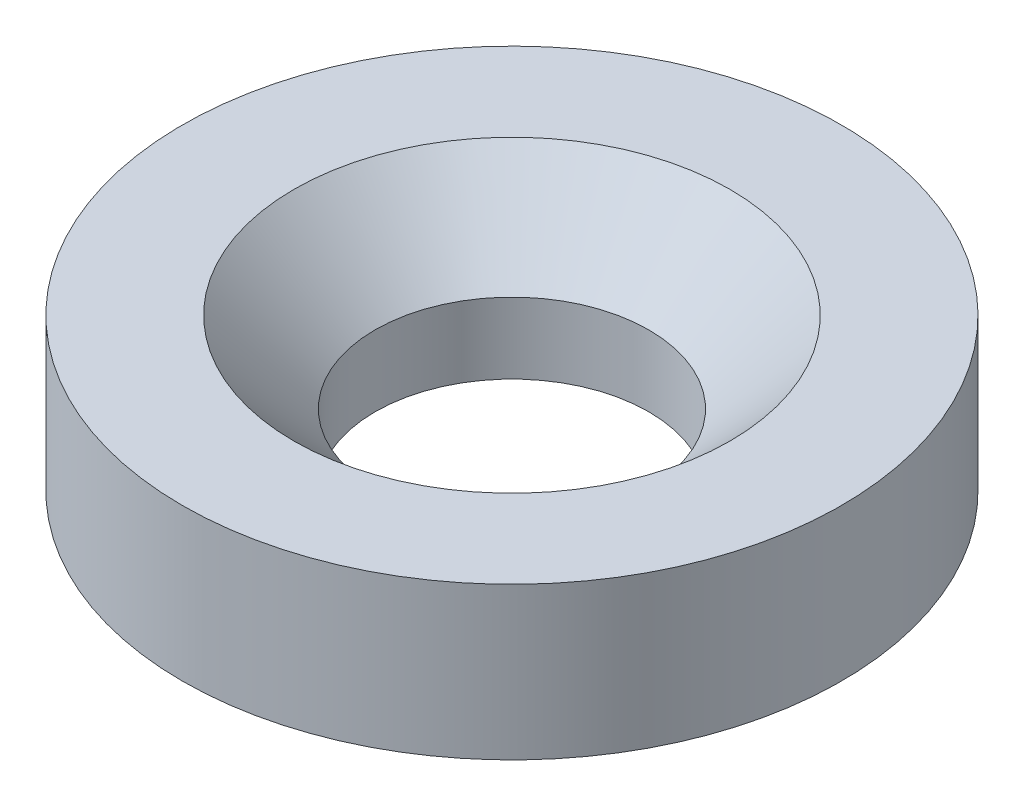
SolidWorks part; units mm, degrees
ref_plane "정면" through (0, 0, 0) normal (0, 0, 1) x (1, 0, 0)
ref_plane "윗면" through (0, 0, 0) normal (0, 1, 0) x (1, 0, 0)
ref_plane "우측면" through (0, 0, 0) normal (1, 0, 0) x (0, 0, -1)
sketch "스케치1" plane through (0, 0, 0) normal (0, 1, 0) x (1, 0, 0)
  circle A0 centre (0, 0) radius 3.25
  dimension "D1" = 6.5
extrude "보스-돌출1" add sketch "스케치1" along normal blind 1.5
sketch "스케치2" plane through (0, 1.5, 0) normal (0, 1, 0) x (1, 0, 0)
  circle A0 centre (0, 0) radius 1.35
  dimension "D1" = 2.7
extrude "컷-돌출1" cut sketch "스케치2" against normal blind 2
chamfer "모따기1" distance 0.8 angle 45 1 edges at (0, 1.5, 1.35)
